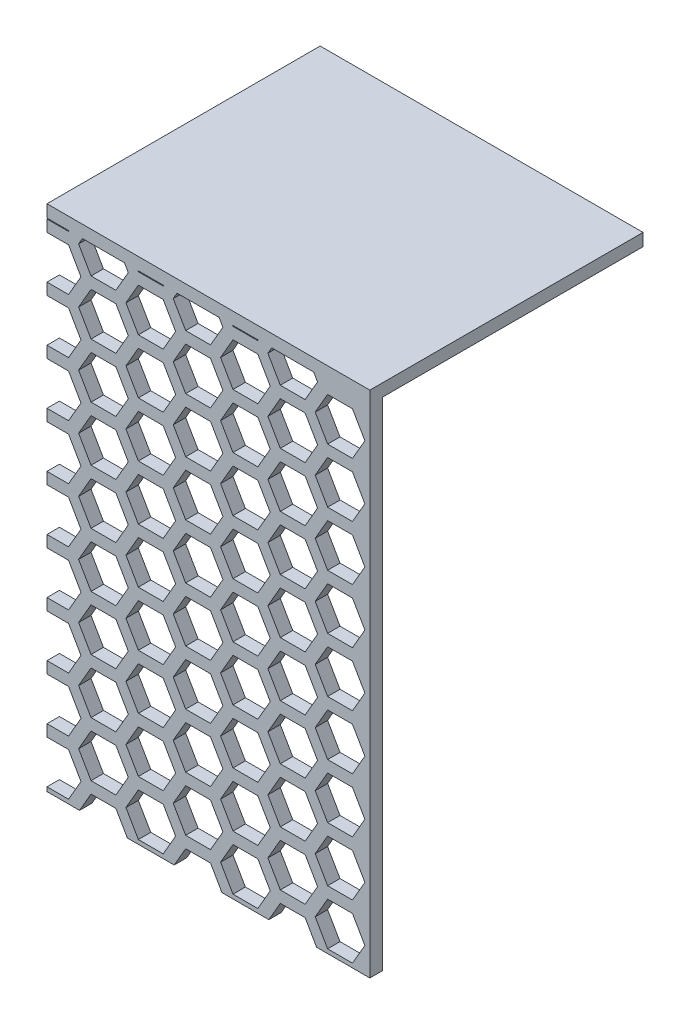
SolidWorks part; units mm, degrees
ref_plane "Front Plane" through (0, 0, 0) normal (0, 0, 1) x (1, 0, 0)
ref_plane "Top Plane" through (0, 0, 0) normal (0, 1, 0) x (1, 0, 0)
ref_plane "Right Plane" through (0, 0, 0) normal (1, 0, 0) x (0, 0, -1)
sketch "Sketch1" plane through (0, 0, 0) normal (0, 0, 1) x (1, 0, 0)
  line L1 (-65, -102.5) -> (65, -102.5)
  line L2 (-65, -102.5) -> (-65, 102.5)
  line L3 (-65, 102.5) -> (65, 102.5)
  line L4 (65, -102.5) -> (65, 102.5)
  line L5 (-65, -102.5) -> (65, 102.5) construction
  line L6 (-65, 102.5) -> (65, -102.5) construction
  point P0 (0, 0)
  dimension "D1" = 205
  dimension "D2" = 130
extrude "Boss-Extrude1" add sketch "Sketch1" along normal blind 5
sketch "Sketch3" plane through (0, 0, 5) normal (0, 0, -1) x (-1, 0, 0)
  line L0 (-65, 102.5) -> (65, 102.5) construction
  line L1 (-43, 83.8397) -> (-48, 92.5)
  line L2 (-48, 92.5) -> (-58, 92.5)
  line L3 (-58, 92.5) -> (-63, 83.8397)
  line L4 (-63, 83.8397) -> (-58, 75.1795)
  line L5 (-58, 75.1795) -> (-48, 75.1795)
  line L6 (-48, 75.1795) -> (-43, 83.8397)
  line L7 (71.3154, 149.8397) -> (66.3154, 158.5)
  line L8 (-65, -102.5) -> (-65, 102.5) construction
  line L9 (-23.9474, 94.8397) -> (-28.9474, 103.5)
  line L10 (-28.9474, 103.5) -> (-38.9474, 103.5)
  line L11 (-38.9474, 103.5) -> (-43.9474, 94.8397)
  line L12 (-43.9474, 94.8397) -> (-38.9474, 86.1795)
  line L13 (-38.9474, 86.1795) -> (-28.9474, 86.1795)
  line L14 (-28.9474, 86.1795) -> (-23.9474, 94.8397)
  line L15 (-4.8949, 105.8397) -> (-9.8949, 114.5)
  line L16 (-9.8949, 114.5) -> (-19.8949, 114.5)
  line L17 (-19.8949, 114.5) -> (-24.8949, 105.8397)
  line L18 (-24.8949, 105.8397) -> (-19.8949, 97.1795)
  line L19 (-19.8949, 97.1795) -> (-9.8949, 97.1795)
  line L20 (-9.8949, 97.1795) -> (-4.8949, 105.8397)
  line L21 (14.1577, 116.8397) -> (9.1577, 125.5)
  line L22 (9.1577, 125.5) -> (-0.8423, 125.5)
  line L23 (-0.8423, 125.5) -> (-5.8423, 116.8397)
  line L24 (-5.8423, 116.8397) -> (-0.8423, 108.1795)
  line L25 (-0.8423, 108.1795) -> (9.1577, 108.1795)
  line L26 (9.1577, 108.1795) -> (14.1577, 116.8397)
  line L27 (33.2102, 127.8397) -> (28.2102, 136.5)
  line L28 (28.2102, 136.5) -> (18.2102, 136.5)
  line L29 (18.2102, 136.5) -> (13.2102, 127.8397)
  line L30 (13.2102, 127.8397) -> (18.2102, 119.1795)
  line L31 (18.2102, 119.1795) -> (28.2102, 119.1795)
  line L32 (28.2102, 119.1795) -> (33.2102, 127.8397)
  line L33 (52.2628, 138.8397) -> (47.2628, 147.5)
  line L34 (47.2628, 147.5) -> (37.2628, 147.5)
  line L35 (37.2628, 147.5) -> (32.2628, 138.8397)
  line L36 (32.2628, 138.8397) -> (37.2628, 130.1795)
  line L37 (37.2628, 130.1795) -> (47.2628, 130.1795)
  line L38 (47.2628, 130.1795) -> (52.2628, 138.8397)
  line L39 (-23.9474, 72.8397) -> (-28.9474, 81.5)
  line L40 (-28.9474, 81.5) -> (-38.9474, 81.5)
  line L41 (-38.9474, 81.5) -> (-43.9474, 72.8397)
  line L42 (-43.9474, 72.8397) -> (-38.9474, 64.1795)
  line L43 (-38.9474, 64.1795) -> (-28.9474, 64.1795)
  line L44 (-28.9474, 64.1795) -> (-23.9474, 72.8397)
  line L45 (-4.8949, 83.8397) -> (-9.8949, 92.5)
  line L46 (-9.8949, 92.5) -> (-19.8949, 92.5)
  line L47 (-19.8949, 92.5) -> (-24.8949, 83.8397)
  line L48 (-24.8949, 83.8397) -> (-19.8949, 75.1795)
  line L49 (-19.8949, 75.1795) -> (-9.8949, 75.1795)
  line L50 (-9.8949, 75.1795) -> (-4.8949, 83.8397)
  line L51 (14.1577, 94.8397) -> (9.1577, 103.5)
  line L52 (9.1577, 103.5) -> (-0.8423, 103.5)
  line L53 (-0.8423, 103.5) -> (-5.8423, 94.8397)
  line L54 (-5.8423, 94.8397) -> (-0.8423, 86.1795)
  line L55 (-0.8423, 86.1795) -> (9.1577, 86.1795)
  line L56 (9.1577, 86.1795) -> (14.1577, 94.8397)
  line L57 (33.2102, 105.8397) -> (28.2102, 114.5)
  line L58 (28.2102, 114.5) -> (18.2102, 114.5)
  line L59 (18.2102, 114.5) -> (13.2102, 105.8397)
  line L60 (13.2102, 105.8397) -> (18.2102, 97.1795)
  line L61 (18.2102, 97.1795) -> (28.2102, 97.1795)
  line L62 (28.2102, 97.1795) -> (33.2102, 105.8397)
  line L63 (52.2628, 116.8397) -> (47.2628, 125.5)
  line L64 (47.2628, 125.5) -> (37.2628, 125.5)
  line L65 (37.2628, 125.5) -> (32.2628, 116.8397)
  line L66 (32.2628, 116.8397) -> (37.2628, 108.1795)
  line L67 (37.2628, 108.1795) -> (47.2628, 108.1795)
  line L68 (47.2628, 108.1795) -> (52.2628, 116.8397)
  line L69 (-23.9474, 50.8397) -> (-28.9474, 59.5)
  line L70 (-28.9474, 59.5) -> (-38.9474, 59.5)
  line L71 (-38.9474, 59.5) -> (-43.9474, 50.8397)
  line L72 (-43.9474, 50.8397) -> (-38.9474, 42.1795)
  line L73 (-38.9474, 42.1795) -> (-28.9474, 42.1795)
  line L74 (-28.9474, 42.1795) -> (-23.9474, 50.8397)
  line L75 (-4.8949, 61.8397) -> (-9.8949, 70.5)
  line L76 (-9.8949, 70.5) -> (-19.8949, 70.5)
  line L77 (-19.8949, 70.5) -> (-24.8949, 61.8397)
  line L78 (-24.8949, 61.8397) -> (-19.8949, 53.1795)
  line L79 (-19.8949, 53.1795) -> (-9.8949, 53.1795)
  line L80 (-9.8949, 53.1795) -> (-4.8949, 61.8397)
  line L81 (14.1577, 72.8397) -> (9.1577, 81.5)
  line L82 (9.1577, 81.5) -> (-0.8423, 81.5)
  line L83 (-0.8423, 81.5) -> (-5.8423, 72.8397)
  line L84 (-5.8423, 72.8397) -> (-0.8423, 64.1795)
  line L85 (-0.8423, 64.1795) -> (9.1577, 64.1795)
  line L86 (9.1577, 64.1795) -> (14.1577, 72.8397)
  line L87 (33.2102, 83.8397) -> (28.2102, 92.5)
  line L88 (28.2102, 92.5) -> (18.2102, 92.5)
  line L89 (18.2102, 92.5) -> (13.2102, 83.8397)
  line L90 (13.2102, 83.8397) -> (18.2102, 75.1795)
  line L91 (18.2102, 75.1795) -> (28.2102, 75.1795)
  line L92 (28.2102, 75.1795) -> (33.2102, 83.8397)
  line L93 (52.2628, 94.8397) -> (47.2628, 103.5)
  line L94 (47.2628, 103.5) -> (37.2628, 103.5)
  line L95 (37.2628, 103.5) -> (32.2628, 94.8397)
  line L96 (32.2628, 94.8397) -> (37.2628, 86.1795)
  line L97 (37.2628, 86.1795) -> (47.2628, 86.1795)
  line L98 (47.2628, 86.1795) -> (52.2628, 94.8397)
  line L99 (-23.9474, 28.8397) -> (-28.9474, 37.5)
  line L100 (-28.9474, 37.5) -> (-38.9474, 37.5)
  line L101 (-38.9474, 37.5) -> (-43.9474, 28.8397)
  line L102 (-43.9474, 28.8397) -> (-38.9474, 20.1795)
  line L103 (-38.9474, 20.1795) -> (-28.9474, 20.1795)
  line L104 (-28.9474, 20.1795) -> (-23.9474, 28.8397)
  line L105 (-4.8949, 39.8397) -> (-9.8949, 48.5)
  line L106 (-9.8949, 48.5) -> (-19.8949, 48.5)
  line L107 (-19.8949, 48.5) -> (-24.8949, 39.8397)
  line L108 (-24.8949, 39.8397) -> (-19.8949, 31.1795)
  line L109 (-19.8949, 31.1795) -> (-9.8949, 31.1795)
  line L110 (-9.8949, 31.1795) -> (-4.8949, 39.8397)
  line L111 (14.1577, 50.8397) -> (9.1577, 59.5)
  line L112 (9.1577, 59.5) -> (-0.8423, 59.5)
  line L113 (-0.8423, 59.5) -> (-5.8423, 50.8397)
  line L114 (-5.8423, 50.8397) -> (-0.8423, 42.1795)
  line L115 (-0.8423, 42.1795) -> (9.1577, 42.1795)
  line L116 (9.1577, 42.1795) -> (14.1577, 50.8397)
  line L117 (33.2102, 61.8397) -> (28.2102, 70.5)
  line L118 (28.2102, 70.5) -> (18.2102, 70.5)
  line L119 (18.2102, 70.5) -> (13.2102, 61.8397)
  line L120 (13.2102, 61.8397) -> (18.2102, 53.1795)
  line L121 (18.2102, 53.1795) -> (28.2102, 53.1795)
  line L122 (28.2102, 53.1795) -> (33.2102, 61.8397)
  line L123 (52.2628, 72.8397) -> (47.2628, 81.5)
  line L124 (47.2628, 81.5) -> (37.2628, 81.5)
  line L125 (37.2628, 81.5) -> (32.2628, 72.8397)
  line L126 (32.2628, 72.8397) -> (37.2628, 64.1795)
  line L127 (37.2628, 64.1795) -> (47.2628, 64.1795)
  line L128 (47.2628, 64.1795) -> (52.2628, 72.8397)
  line L129 (-23.9474, 6.8397) -> (-28.9474, 15.5)
  line L130 (-28.9474, 15.5) -> (-38.9474, 15.5)
  line L131 (-38.9474, 15.5) -> (-43.9474, 6.8397)
  line L132 (-43.9474, 6.8397) -> (-38.9474, -1.8205)
  line L133 (-38.9474, -1.8205) -> (-28.9474, -1.8205)
  line L134 (-28.9474, -1.8205) -> (-23.9474, 6.8397)
  line L135 (-4.8949, 17.8397) -> (-9.8949, 26.5)
  line L136 (-9.8949, 26.5) -> (-19.8949, 26.5)
  line L137 (-19.8949, 26.5) -> (-24.8949, 17.8397)
  line L138 (-24.8949, 17.8397) -> (-19.8949, 9.1795)
  line L139 (-19.8949, 9.1795) -> (-9.8949, 9.1795)
  line L140 (-9.8949, 9.1795) -> (-4.8949, 17.8397)
  line L141 (14.1577, 28.8397) -> (9.1577, 37.5)
  line L142 (9.1577, 37.5) -> (-0.8423, 37.5)
  line L143 (-0.8423, 37.5) -> (-5.8423, 28.8397)
  line L144 (-5.8423, 28.8397) -> (-0.8423, 20.1795)
  line L145 (-0.8423, 20.1795) -> (9.1577, 20.1795)
  line L146 (9.1577, 20.1795) -> (14.1577, 28.8397)
  line L147 (33.2102, 39.8397) -> (28.2102, 48.5)
  line L148 (28.2102, 48.5) -> (18.2102, 48.5)
  line L149 (18.2102, 48.5) -> (13.2102, 39.8397)
  line L150 (13.2102, 39.8397) -> (18.2102, 31.1795)
  line L151 (18.2102, 31.1795) -> (28.2102, 31.1795)
  line L152 (28.2102, 31.1795) -> (33.2102, 39.8397)
  line L153 (52.2628, 50.8397) -> (47.2628, 59.5)
  line L154 (47.2628, 59.5) -> (37.2628, 59.5)
  line L155 (37.2628, 59.5) -> (32.2628, 50.8397)
  line L156 (32.2628, 50.8397) -> (37.2628, 42.1795)
  line L157 (37.2628, 42.1795) -> (47.2628, 42.1795)
  line L158 (47.2628, 42.1795) -> (52.2628, 50.8397)
  line L159 (-23.9474, -15.1603) -> (-28.9474, -6.5)
  line L160 (-28.9474, -6.5) -> (-38.9474, -6.5)
  line L161 (-38.9474, -6.5) -> (-43.9474, -15.1603)
  line L162 (-43.9474, -15.1603) -> (-38.9474, -23.8205)
  line L163 (-38.9474, -23.8205) -> (-28.9474, -23.8205)
  line L164 (-28.9474, -23.8205) -> (-23.9474, -15.1603)
  line L165 (-4.8949, -4.1603) -> (-9.8949, 4.5)
  line L166 (-9.8949, 4.5) -> (-19.8949, 4.5)
  line L167 (-19.8949, 4.5) -> (-24.8949, -4.1603)
  line L168 (-24.8949, -4.1603) -> (-19.8949, -12.8205)
  line L169 (-19.8949, -12.8205) -> (-9.8949, -12.8205)
  line L170 (-9.8949, -12.8205) -> (-4.8949, -4.1603)
  line L171 (14.1577, 6.8397) -> (9.1577, 15.5)
  line L172 (9.1577, 15.5) -> (-0.8423, 15.5)
  line L173 (-0.8423, 15.5) -> (-5.8423, 6.8397)
  line L174 (-5.8423, 6.8397) -> (-0.8423, -1.8205)
  line L175 (-0.8423, -1.8205) -> (9.1577, -1.8205)
  line L176 (9.1577, -1.8205) -> (14.1577, 6.8397)
  line L177 (33.2102, 17.8397) -> (28.2102, 26.5)
  line L178 (28.2102, 26.5) -> (18.2102, 26.5)
  line L179 (18.2102, 26.5) -> (13.2102, 17.8397)
  line L180 (13.2102, 17.8397) -> (18.2102, 9.1795)
  line L181 (18.2102, 9.1795) -> (28.2102, 9.1795)
  line L182 (28.2102, 9.1795) -> (33.2102, 17.8397)
  line L183 (52.2628, 28.8397) -> (47.2628, 37.5)
  line L184 (47.2628, 37.5) -> (37.2628, 37.5)
  line L185 (37.2628, 37.5) -> (32.2628, 28.8397)
  line L186 (32.2628, 28.8397) -> (37.2628, 20.1795)
  line L187 (37.2628, 20.1795) -> (47.2628, 20.1795)
  line L188 (47.2628, 20.1795) -> (52.2628, 28.8397)
  line L189 (-23.9474, -37.1603) -> (-28.9474, -28.5)
  line L190 (-28.9474, -28.5) -> (-38.9474, -28.5)
  line L191 (-38.9474, -28.5) -> (-43.9474, -37.1603)
  line L192 (-43.9474, -37.1603) -> (-38.9474, -45.8205)
  line L193 (-38.9474, -45.8205) -> (-28.9474, -45.8205)
  line L194 (-28.9474, -45.8205) -> (-23.9474, -37.1603)
  line L195 (-4.8949, -26.1603) -> (-9.8949, -17.5)
  line L196 (-9.8949, -17.5) -> (-19.8949, -17.5)
  line L197 (-19.8949, -17.5) -> (-24.8949, -26.1603)
  line L198 (-24.8949, -26.1603) -> (-19.8949, -34.8205)
  line L199 (-19.8949, -34.8205) -> (-9.8949, -34.8205)
  line L200 (-9.8949, -34.8205) -> (-4.8949, -26.1603)
  line L201 (14.1577, -15.1603) -> (9.1577, -6.5)
  line L202 (9.1577, -6.5) -> (-0.8423, -6.5)
  line L203 (-0.8423, -6.5) -> (-5.8423, -15.1603)
  line L204 (-5.8423, -15.1603) -> (-0.8423, -23.8205)
  line L205 (-0.8423, -23.8205) -> (9.1577, -23.8205)
  line L206 (9.1577, -23.8205) -> (14.1577, -15.1603)
  line L207 (33.2102, -4.1603) -> (28.2102, 4.5)
  line L208 (28.2102, 4.5) -> (18.2102, 4.5)
  line L209 (18.2102, 4.5) -> (13.2102, -4.1603)
  line L210 (13.2102, -4.1603) -> (18.2102, -12.8205)
  line L211 (18.2102, -12.8205) -> (28.2102, -12.8205)
  line L212 (28.2102, -12.8205) -> (33.2102, -4.1603)
  line L213 (52.2628, 6.8397) -> (47.2628, 15.5)
  line L214 (47.2628, 15.5) -> (37.2628, 15.5)
  line L215 (37.2628, 15.5) -> (32.2628, 6.8397)
  line L216 (32.2628, 6.8397) -> (37.2628, -1.8205)
  line L217 (37.2628, -1.8205) -> (47.2628, -1.8205)
  line L218 (47.2628, -1.8205) -> (52.2628, 6.8397)
  line L219 (-23.9474, -59.1603) -> (-28.9474, -50.5)
  line L220 (-28.9474, -50.5) -> (-38.9474, -50.5)
  line L221 (-38.9474, -50.5) -> (-43.9474, -59.1603)
  line L222 (-43.9474, -59.1603) -> (-38.9474, -67.8205)
  line L223 (-38.9474, -67.8205) -> (-28.9474, -67.8205)
  line L224 (-28.9474, -67.8205) -> (-23.9474, -59.1603)
  line L225 (-4.8949, -48.1603) -> (-9.8949, -39.5)
  line L226 (-9.8949, -39.5) -> (-19.8949, -39.5)
  line L227 (-19.8949, -39.5) -> (-24.8949, -48.1603)
  line L228 (-24.8949, -48.1603) -> (-19.8949, -56.8205)
  line L229 (-19.8949, -56.8205) -> (-9.8949, -56.8205)
  line L230 (-9.8949, -56.8205) -> (-4.8949, -48.1603)
  line L231 (14.1577, -37.1603) -> (9.1577, -28.5)
  line L232 (9.1577, -28.5) -> (-0.8423, -28.5)
  line L233 (-0.8423, -28.5) -> (-5.8423, -37.1603)
  line L234 (-5.8423, -37.1603) -> (-0.8423, -45.8205)
  line L235 (-0.8423, -45.8205) -> (9.1577, -45.8205)
  line L236 (9.1577, -45.8205) -> (14.1577, -37.1603)
  line L237 (33.2102, -26.1603) -> (28.2102, -17.5)
  line L238 (28.2102, -17.5) -> (18.2102, -17.5)
  line L239 (18.2102, -17.5) -> (13.2102, -26.1603)
  line L240 (13.2102, -26.1603) -> (18.2102, -34.8205)
  line L241 (18.2102, -34.8205) -> (28.2102, -34.8205)
  line L242 (28.2102, -34.8205) -> (33.2102, -26.1603)
  line L243 (52.2628, -15.1603) -> (47.2628, -6.5)
  line L244 (47.2628, -6.5) -> (37.2628, -6.5)
  line L245 (37.2628, -6.5) -> (32.2628, -15.1603)
  line L246 (32.2628, -15.1603) -> (37.2628, -23.8205)
  line L247 (37.2628, -23.8205) -> (47.2628, -23.8205)
  line L248 (47.2628, -23.8205) -> (52.2628, -15.1603)
  line L249 (-23.9474, -81.1603) -> (-28.9474, -72.5)
  line L250 (-28.9474, -72.5) -> (-38.9474, -72.5)
  line L251 (-38.9474, -72.5) -> (-43.9474, -81.1603)
  line L252 (-43.9474, -81.1603) -> (-38.9474, -89.8205)
  line L253 (-38.9474, -89.8205) -> (-28.9474, -89.8205)
  line L254 (-28.9474, -89.8205) -> (-23.9474, -81.1603)
  line L255 (-4.8949, -70.1603) -> (-9.8949, -61.5)
  line L256 (-9.8949, -61.5) -> (-19.8949, -61.5)
  line L257 (-19.8949, -61.5) -> (-24.8949, -70.1603)
  line L258 (-24.8949, -70.1603) -> (-19.8949, -78.8205)
  line L259 (-19.8949, -78.8205) -> (-9.8949, -78.8205)
  line L260 (-9.8949, -78.8205) -> (-4.8949, -70.1603)
  line L261 (14.1577, -59.1603) -> (9.1577, -50.5)
  line L262 (9.1577, -50.5) -> (-0.8423, -50.5)
  line L263 (-0.8423, -50.5) -> (-5.8423, -59.1603)
  line L264 (-5.8423, -59.1603) -> (-0.8423, -67.8205)
  line L265 (-0.8423, -67.8205) -> (9.1577, -67.8205)
  line L266 (9.1577, -67.8205) -> (14.1577, -59.1603)
  line L267 (33.2102, -48.1603) -> (28.2102, -39.5)
  line L268 (28.2102, -39.5) -> (18.2102, -39.5)
  line L269 (18.2102, -39.5) -> (13.2102, -48.1603)
  line L270 (13.2102, -48.1603) -> (18.2102, -56.8205)
  line L271 (18.2102, -56.8205) -> (28.2102, -56.8205)
  line L272 (28.2102, -56.8205) -> (33.2102, -48.1603)
  line L273 (52.2628, -37.1603) -> (47.2628, -28.5)
  line L274 (47.2628, -28.5) -> (37.2628, -28.5)
  line L275 (37.2628, -28.5) -> (32.2628, -37.1603)
  line L276 (32.2628, -37.1603) -> (37.2628, -45.8205)
  line L277 (37.2628, -45.8205) -> (47.2628, -45.8205)
  line L278 (47.2628, -45.8205) -> (52.2628, -37.1603)
  line L279 (-23.9474, -103.1603) -> (-28.9474, -94.5)
  line L280 (-28.9474, -94.5) -> (-38.9474, -94.5)
  line L281 (-38.9474, -94.5) -> (-43.9474, -103.1603)
  line L282 (-43.9474, -103.1603) -> (-38.9474, -111.8205)
  line L283 (-38.9474, -111.8205) -> (-28.9474, -111.8205)
  line L284 (-28.9474, -111.8205) -> (-23.9474, -103.1603)
  line L285 (-4.8949, -92.1603) -> (-9.8949, -83.5)
  line L286 (-9.8949, -83.5) -> (-19.8949, -83.5)
  line L287 (-19.8949, -83.5) -> (-24.8949, -92.1603)
  line L288 (-24.8949, -92.1603) -> (-19.8949, -100.8205)
  line L289 (-19.8949, -100.8205) -> (-9.8949, -100.8205)
  line L290 (-9.8949, -100.8205) -> (-4.8949, -92.1603)
  line L291 (14.1577, -81.1603) -> (9.1577, -72.5)
  line L292 (9.1577, -72.5) -> (-0.8423, -72.5)
  line L293 (-0.8423, -72.5) -> (-5.8423, -81.1603)
  line L294 (-5.8423, -81.1603) -> (-0.8423, -89.8205)
  line L295 (-0.8423, -89.8205) -> (9.1577, -89.8205)
  line L296 (9.1577, -89.8205) -> (14.1577, -81.1603)
  line L297 (33.2102, -70.1603) -> (28.2102, -61.5)
  line L298 (28.2102, -61.5) -> (18.2102, -61.5)
  line L299 (18.2102, -61.5) -> (13.2102, -70.1603)
  line L300 (13.2102, -70.1603) -> (18.2102, -78.8205)
  line L301 (18.2102, -78.8205) -> (28.2102, -78.8205)
  line L302 (28.2102, -78.8205) -> (33.2102, -70.1603)
  line L303 (52.2628, -59.1603) -> (47.2628, -50.5)
  line L304 (47.2628, -50.5) -> (37.2628, -50.5)
  line L305 (37.2628, -50.5) -> (32.2628, -59.1603)
  line L306 (32.2628, -59.1603) -> (37.2628, -67.8205)
  line L307 (37.2628, -67.8205) -> (47.2628, -67.8205)
  line L308 (47.2628, -67.8205) -> (52.2628, -59.1603)
  line L309 (-23.9474, -125.1603) -> (-28.9474, -116.5)
  line L310 (-28.9474, -116.5) -> (-38.9474, -116.5)
  line L311 (-38.9474, -116.5) -> (-43.9474, -125.1603)
  line L312 (-43.9474, -125.1603) -> (-38.9474, -133.8205)
  line L313 (-38.9474, -133.8205) -> (-28.9474, -133.8205)
  line L314 (-28.9474, -133.8205) -> (-23.9474, -125.1603)
  line L315 (-4.8949, -114.1603) -> (-9.8949, -105.5)
  line L316 (-9.8949, -105.5) -> (-19.8949, -105.5)
  line L317 (-19.8949, -105.5) -> (-24.8949, -114.1603)
  line L318 (-24.8949, -114.1603) -> (-19.8949, -122.8205)
  line L319 (-19.8949, -122.8205) -> (-9.8949, -122.8205)
  line L320 (-9.8949, -122.8205) -> (-4.8949, -114.1603)
  line L321 (14.1577, -103.1603) -> (9.1577, -94.5)
  line L322 (9.1577, -94.5) -> (-0.8423, -94.5)
  line L323 (-0.8423, -94.5) -> (-5.8423, -103.1603)
  line L324 (-5.8423, -103.1603) -> (-0.8423, -111.8205)
  line L325 (-0.8423, -111.8205) -> (9.1577, -111.8205)
  line L326 (9.1577, -111.8205) -> (14.1577, -103.1603)
  line L327 (33.2102, -92.1603) -> (28.2102, -83.5)
  line L328 (28.2102, -83.5) -> (18.2102, -83.5)
  line L329 (18.2102, -83.5) -> (13.2102, -92.1603)
  line L330 (13.2102, -92.1603) -> (18.2102, -100.8205)
  line L331 (18.2102, -100.8205) -> (28.2102, -100.8205)
  line L332 (28.2102, -100.8205) -> (33.2102, -92.1603)
  line L333 (52.2628, -81.1603) -> (47.2628, -72.5)
  line L334 (47.2628, -72.5) -> (37.2628, -72.5)
  line L335 (37.2628, -72.5) -> (32.2628, -81.1603)
  line L336 (32.2628, -81.1603) -> (37.2628, -89.8205)
  line L337 (37.2628, -89.8205) -> (47.2628, -89.8205)
  line L338 (47.2628, -89.8205) -> (52.2628, -81.1603)
  line L339 (-23.9474, -147.1603) -> (-28.9474, -138.5)
  line L340 (-28.9474, -138.5) -> (-38.9474, -138.5)
  line L341 (-38.9474, -138.5) -> (-43.9474, -147.1603)
  line L342 (-43.9474, -147.1603) -> (-38.9474, -155.8205)
  line L343 (-38.9474, -155.8205) -> (-28.9474, -155.8205)
  line L344 (-28.9474, -155.8205) -> (-23.9474, -147.1603)
  line L345 (-4.8949, -136.1603) -> (-9.8949, -127.5)
  line L346 (-9.8949, -127.5) -> (-19.8949, -127.5)
  line L347 (-19.8949, -127.5) -> (-24.8949, -136.1603)
  line L348 (-24.8949, -136.1603) -> (-19.8949, -144.8205)
  line L349 (-19.8949, -144.8205) -> (-9.8949, -144.8205)
  line L350 (-9.8949, -144.8205) -> (-4.8949, -136.1603)
  line L351 (14.1577, -125.1603) -> (9.1577, -116.5)
  line L352 (9.1577, -116.5) -> (-0.8423, -116.5)
  line L353 (-0.8423, -116.5) -> (-5.8423, -125.1603)
  line L354 (-5.8423, -125.1603) -> (-0.8423, -133.8205)
  line L355 (-0.8423, -133.8205) -> (9.1577, -133.8205)
  line L356 (9.1577, -133.8205) -> (14.1577, -125.1603)
  line L357 (33.2102, -114.1603) -> (28.2102, -105.5)
  line L358 (28.2102, -105.5) -> (18.2102, -105.5)
  line L359 (18.2102, -105.5) -> (13.2102, -114.1603)
  line L360 (13.2102, -114.1603) -> (18.2102, -122.8205)
  line L361 (18.2102, -122.8205) -> (28.2102, -122.8205)
  line L362 (28.2102, -122.8205) -> (33.2102, -114.1603)
  line L363 (52.2628, -103.1603) -> (47.2628, -94.5)
  line L364 (47.2628, -94.5) -> (37.2628, -94.5)
  line L365 (37.2628, -94.5) -> (32.2628, -103.1603)
  line L366 (32.2628, -103.1603) -> (37.2628, -111.8205)
  line L367 (37.2628, -111.8205) -> (47.2628, -111.8205)
  line L368 (47.2628, -111.8205) -> (52.2628, -103.1603)
  line L369 (-43, 61.8397) -> (-48, 70.5)
  line L370 (-48, 70.5) -> (-58, 70.5)
  line L371 (-58, 70.5) -> (-63, 61.8397)
  line L372 (-63, 61.8397) -> (-58, 53.1795)
  line L373 (-58, 53.1795) -> (-48, 53.1795)
  line L374 (-48, 53.1795) -> (-43, 61.8397)
  line L375 (-43, 39.8397) -> (-48, 48.5)
  line L376 (-48, 48.5) -> (-58, 48.5)
  line L377 (-58, 48.5) -> (-63, 39.8397)
  line L378 (-63, 39.8397) -> (-58, 31.1795)
  line L379 (-58, 31.1795) -> (-48, 31.1795)
  line L380 (-48, 31.1795) -> (-43, 39.8397)
  line L381 (-43, 17.8397) -> (-48, 26.5)
  line L382 (-48, 26.5) -> (-58, 26.5)
  line L383 (-58, 26.5) -> (-63, 17.8397)
  line L384 (-63, 17.8397) -> (-58, 9.1795)
  line L385 (-58, 9.1795) -> (-48, 9.1795)
  line L386 (-48, 9.1795) -> (-43, 17.8397)
  line L387 (-43, -4.1603) -> (-48, 4.5)
  line L388 (-48, 4.5) -> (-58, 4.5)
  line L389 (-58, 4.5) -> (-63, -4.1603)
  line L390 (-63, -4.1603) -> (-58, -12.8205)
  line L391 (-58, -12.8205) -> (-48, -12.8205)
  line L392 (-48, -12.8205) -> (-43, -4.1603)
  line L393 (-43, -26.1603) -> (-48, -17.5)
  line L394 (-48, -17.5) -> (-58, -17.5)
  line L395 (-58, -17.5) -> (-63, -26.1603)
  line L396 (-63, -26.1603) -> (-58, -34.8205)
  line L397 (-58, -34.8205) -> (-48, -34.8205)
  line L398 (-48, -34.8205) -> (-43, -26.1603)
  line L399 (-43, -48.1603) -> (-48, -39.5)
  line L400 (-48, -39.5) -> (-58, -39.5)
  line L401 (-58, -39.5) -> (-63, -48.1603)
  line L402 (-63, -48.1603) -> (-58, -56.8205)
  line L403 (-58, -56.8205) -> (-48, -56.8205)
  line L404 (-48, -56.8205) -> (-43, -48.1603)
  line L405 (-43, -70.1603) -> (-48, -61.5)
  line L406 (-48, -61.5) -> (-58, -61.5)
  line L407 (-58, -61.5) -> (-63, -70.1603)
  line L408 (-63, -70.1603) -> (-58, -78.8205)
  line L409 (-58, -78.8205) -> (-48, -78.8205)
  line L410 (-48, -78.8205) -> (-43, -70.1603)
  line L411 (-43, -92.1603) -> (-48, -83.5)
  line L412 (-48, -83.5) -> (-58, -83.5)
  line L413 (-58, -83.5) -> (-63, -92.1603)
  line L414 (-63, -92.1603) -> (-58, -100.8205)
  line L415 (-58, -100.8205) -> (-48, -100.8205)
  line L416 (-48, -100.8205) -> (-43, -92.1603)
  line L417 (-43, -114.1603) -> (-48, -105.5)
  line L418 (-48, -105.5) -> (-58, -105.5)
  line L419 (-58, -105.5) -> (-63, -114.1603)
  line L420 (-63, -114.1603) -> (-58, -122.8205)
  line L421 (-58, -122.8205) -> (-48, -122.8205)
  line L422 (-48, -122.8205) -> (-43, -114.1603)
  line L423 (-43, -136.1603) -> (-48, -127.5)
  line L424 (-48, -127.5) -> (-58, -127.5)
  line L425 (-58, -127.5) -> (-63, -136.1603)
  line L426 (-63, -136.1603) -> (-58, -144.8205)
  line L427 (-58, -144.8205) -> (-48, -144.8205)
  line L428 (-48, -144.8205) -> (-43, -136.1603)
  line L429 (-43, -158.1603) -> (-48, -149.5)
  line L430 (-48, -149.5) -> (-58, -149.5)
  line L431 (-58, -149.5) -> (-63, -158.1603)
  line L432 (-63, -158.1603) -> (-58, -166.8205)
  line L433 (-58, -166.8205) -> (-48, -166.8205)
  line L434 (-48, -166.8205) -> (-43, -158.1603)
  line L435 (-43, 83.8397) -> (-23.9474, 94.8397) construction
  line L436 (66.3154, 158.5) -> (56.3154, 158.5)
  line L437 (56.3154, 158.5) -> (51.3154, 149.8397)
  line L438 (51.3154, 149.8397) -> (56.3154, 141.1795)
  line L439 (56.3154, 141.1795) -> (66.3154, 141.1795)
  line L440 (66.3154, 141.1795) -> (71.3154, 149.8397)
  line L441 (71.3154, 127.8397) -> (66.3154, 136.5)
  line L442 (66.3154, 136.5) -> (56.3154, 136.5)
  line L443 (56.3154, 136.5) -> (51.3154, 127.8397)
  line L444 (51.3154, 127.8397) -> (56.3154, 119.1795)
  line L445 (56.3154, 119.1795) -> (66.3154, 119.1795)
  line L446 (66.3154, 119.1795) -> (71.3154, 127.8397)
  line L447 (71.3154, 105.8397) -> (66.3154, 114.5)
  line L448 (66.3154, 114.5) -> (56.3154, 114.5)
  line L449 (56.3154, 114.5) -> (51.3154, 105.8397)
  line L450 (51.3154, 105.8397) -> (56.3154, 97.1795)
  line L451 (56.3154, 97.1795) -> (66.3154, 97.1795)
  line L452 (66.3154, 97.1795) -> (71.3154, 105.8397)
  line L453 (71.3154, 83.8397) -> (66.3154, 92.5)
  line L454 (66.3154, 92.5) -> (56.3154, 92.5)
  line L455 (56.3154, 92.5) -> (51.3154, 83.8397)
  line L456 (51.3154, 83.8397) -> (56.3154, 75.1795)
  line L457 (56.3154, 75.1795) -> (66.3154, 75.1795)
  line L458 (66.3154, 75.1795) -> (71.3154, 83.8397)
  line L459 (71.3154, 61.8397) -> (66.3154, 70.5)
  line L460 (66.3154, 70.5) -> (56.3154, 70.5)
  line L461 (56.3154, 70.5) -> (51.3154, 61.8397)
  line L462 (51.3154, 61.8397) -> (56.3154, 53.1795)
  line L463 (56.3154, 53.1795) -> (66.3154, 53.1795)
  line L464 (66.3154, 53.1795) -> (71.3154, 61.8397)
  line L465 (71.3154, 39.8397) -> (66.3154, 48.5)
  line L466 (66.3154, 48.5) -> (56.3154, 48.5)
  line L467 (56.3154, 48.5) -> (51.3154, 39.8397)
  line L468 (51.3154, 39.8397) -> (56.3154, 31.1795)
  line L469 (56.3154, 31.1795) -> (66.3154, 31.1795)
  line L470 (66.3154, 31.1795) -> (71.3154, 39.8397)
  line L471 (71.3154, 17.8397) -> (66.3154, 26.5)
  line L472 (66.3154, 26.5) -> (56.3154, 26.5)
  line L473 (56.3154, 26.5) -> (51.3154, 17.8397)
  line L474 (51.3154, 17.8397) -> (56.3154, 9.1795)
  line L475 (56.3154, 9.1795) -> (66.3154, 9.1795)
  line L476 (66.3154, 9.1795) -> (71.3154, 17.8397)
  line L477 (71.3154, -4.1603) -> (66.3154, 4.5)
  line L478 (66.3154, 4.5) -> (56.3154, 4.5)
  line L479 (56.3154, 4.5) -> (51.3154, -4.1603)
  line L480 (51.3154, -4.1603) -> (56.3154, -12.8205)
  line L481 (56.3154, -12.8205) -> (66.3154, -12.8205)
  line L482 (66.3154, -12.8205) -> (71.3154, -4.1603)
  line L483 (71.3154, -26.1603) -> (66.3154, -17.5)
  line L484 (66.3154, -17.5) -> (56.3154, -17.5)
  line L485 (56.3154, -17.5) -> (51.3154, -26.1603)
  line L486 (51.3154, -26.1603) -> (56.3154, -34.8205)
  line L487 (56.3154, -34.8205) -> (66.3154, -34.8205)
  line L488 (66.3154, -34.8205) -> (71.3154, -26.1603)
  line L489 (71.3154, -48.1603) -> (66.3154, -39.5)
  line L490 (66.3154, -39.5) -> (56.3154, -39.5)
  line L491 (56.3154, -39.5) -> (51.3154, -48.1603)
  line L492 (51.3154, -48.1603) -> (56.3154, -56.8205)
  line L493 (56.3154, -56.8205) -> (66.3154, -56.8205)
  line L494 (66.3154, -56.8205) -> (71.3154, -48.1603)
  line L495 (71.3154, -70.1603) -> (66.3154, -61.5)
  line L496 (66.3154, -61.5) -> (56.3154, -61.5)
  line L497 (56.3154, -61.5) -> (51.3154, -70.1603)
  line L498 (51.3154, -70.1603) -> (56.3154, -78.8205)
  line L499 (56.3154, -78.8205) -> (66.3154, -78.8205)
  line L500 (66.3154, -78.8205) -> (71.3154, -70.1603)
  line L501 (71.3154, -92.1603) -> (66.3154, -83.5)
  line L502 (66.3154, -83.5) -> (56.3154, -83.5)
  line L503 (56.3154, -83.5) -> (51.3154, -92.1603)
  line L504 (51.3154, -92.1603) -> (56.3154, -100.8205)
  line L505 (56.3154, -100.8205) -> (66.3154, -100.8205)
  line L506 (66.3154, -100.8205) -> (71.3154, -92.1603)
  circle A0 centre (-53, 83.8397) radius 8.6603 construction
  dimension "D1" = 10
  dimension "D2" = 10
  dimension "D3" = 12
  dimension "D6" = 22
  dimension "D4" = 7
  dimension "D5" = 12
extrude "Cut-Extrude4" cut sketch "Sketch3" along normal blind 90
sketch "Sketch2" plane through (0, 0, 0) normal (0, 0, -1) x (-1, 0, 0)
  line L0 (65, -100.8205) -> (65, -102.5) construction
  line L1 (-65, 102.5) -> (65, 102.5)
  line L2 (-65, 102.5) -> (-65, 97.5)
  line L3 (-65, 97.5) -> (65, 97.5)
  line L4 (65, 102.5) -> (65, 97.5)
  dimension "D1" = 5
extrude "Boss-Extrude2" add sketch "Sketch2" along normal blind 105 and the other way blind 5
